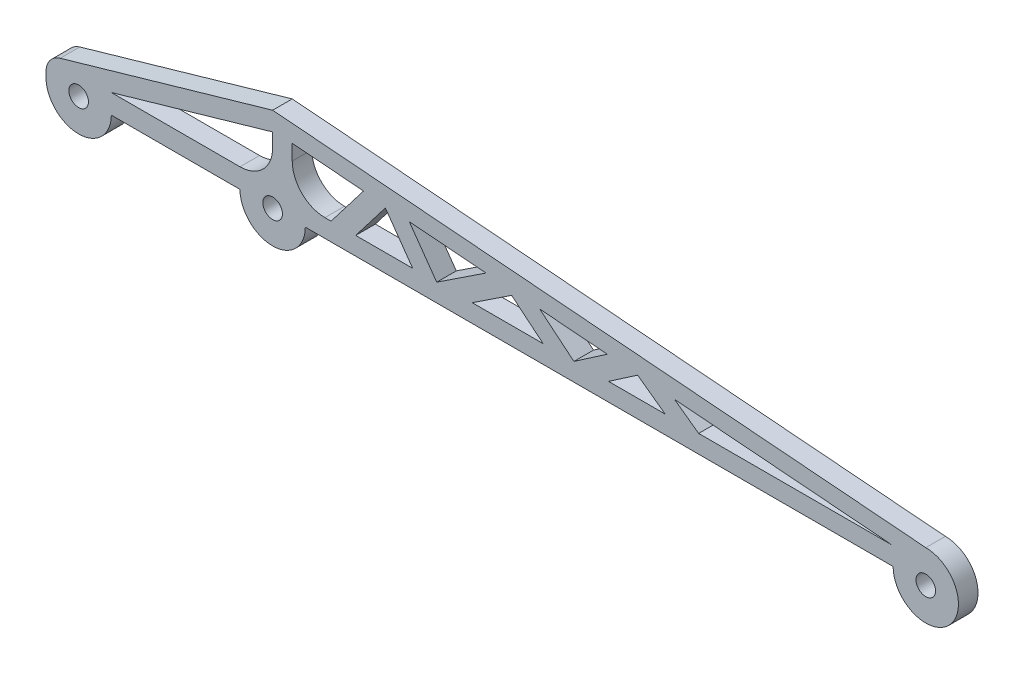
SolidWorks part; units mm, degrees
ref_plane "Front Plane" through (0, 0, 0) normal (0, 0, 1) x (1, 0, 0)
ref_plane "Top Plane" through (0, 0, 0) normal (0, 1, 0) x (1, 0, 0)
ref_plane "Right Plane" through (0, 0, 0) normal (1, 0, 0) x (0, 0, -1)
sketch "Sketch1" plane through (0, 0, 0) normal (0, 0, 1) x (1, 0, 0)
  line L0 (-47.3627, 0) -> (63.0898, 0) construction
  line L1 (-34.7, 0) -> (-34.7, 3)
  line L2 (-34.7, 3) -> (0, 13)
  line L3 (0, 13) -> (100, 5)
  line L4 (-24.7, 0) -> (-5, 0)
  line L5 (5, 0) -> (95, 0)
  line L6 (0, -28.2526) -> (0, 43.1323) construction
  line L7 (-24.7, 3) -> (0, 10.1182)
  line L8 (0, 10.1182) -> (0, 3)
  line L9 (0, 3) -> (-24.7, 3)
  line L10 (3, 10.1182) -> (3, 2.7582)
  line L11 (3, 2.7582) -> (8.9362, 2.7582)
  line L12 (95, 2.7582) -> (61.5197, 5.4366)
  line L13 (8.9362, 2.7582) -> (13.917, 9.2448)
  line L14 (12.7186, 2.7582) -> (17.2596, 8.6719)
  line L15 (13.917, 9.2448) -> (3, 10.1182)
  line L16 (12.7186, 2.7582) -> (21.445, 2.7582)
  line L17 (17.2596, 8.6719) -> (21.445, 2.7582)
  line L18 (20.9263, 8.684) -> (25.1203, 2.7582)
  line L19 (30.5619, 2.7582) -> (41.416, 2.7582)
  line L20 (25.1203, 2.7582) -> (32.6666, 7.7448)
  line L21 (30.5619, 2.7582) -> (36.5914, 6.7426)
  line L22 (32.6666, 7.7448) -> (20.9263, 8.684)
  line L23 (36.5914, 6.7426) -> (41.416, 2.7582)
  line L24 (40.8852, 7.0873) -> (46.1273, 2.7582)
  line L25 (51.4298, 2.7582) -> (60.1041, 2.7582)
  line L26 (46.1273, 2.7582) -> (51.2305, 6.2597)
  line L27 (51.4298, 2.7582) -> (55.8803, 5.8119)
  line L28 (51.2305, 6.2597) -> (40.8852, 7.0873)
  line L29 (55.8803, 5.8119) -> (60.1041, 2.7582)
  line L30 (61.5197, 5.4366) -> (65.2244, 2.7582)
  line L31 (65.2244, 2.7582) -> (95, 2.7582)
  arc A0 (-34.7, 0) -> (-24.7, 0) centre (-29.7, 0) ccw
  arc A1 (-5, 0) -> (5, 0) centre (0, 0) ccw
  arc A2 (95, 0) -> (100, 5) centre (100, 0) ccw
  circle A3 centre (-29.7, 0) radius 1.5
  circle A4 centre (0, 0) radius 1.5
  circle A5 centre (100, 0) radius 1.5
  point P21 (3, 6.4382)
  point P38 (43.5062, 4.9227)
  dimension "D3" = 5
  dimension "D4" = 5
  dimension "D5" = 5
  dimension "D6" = 3
  dimension "D7" = 3
  dimension "D8" = 3
  dimension "D1" = 29.7
  dimension "D2" = 100
  dimension "D9" = 34.7
  dimension "D10" = 100
  dimension "D11" = 13
  dimension "D12" = 3
  dimension "D13" = 3
  dimension "D14" = 3
  dimension "D15" = 3
  dimension "D16" = 3
  dimension "D17" = 3
  dimension "D18" = 3
  dimension "D19" = 3
  dimension "D20" = 3
extrude "Boss-Extrude1" add sketch "Sketch1" along normal blind 3
fillet "Fillet1" radius 3 1 edges at (-34.7, 3, 1.5)
fillet "Fillet2" radius 5 1 edges at (0, 3, 1.5)
fillet "Fillet3" radius 5 1 edges at (3, 2.7582, 1.5)
